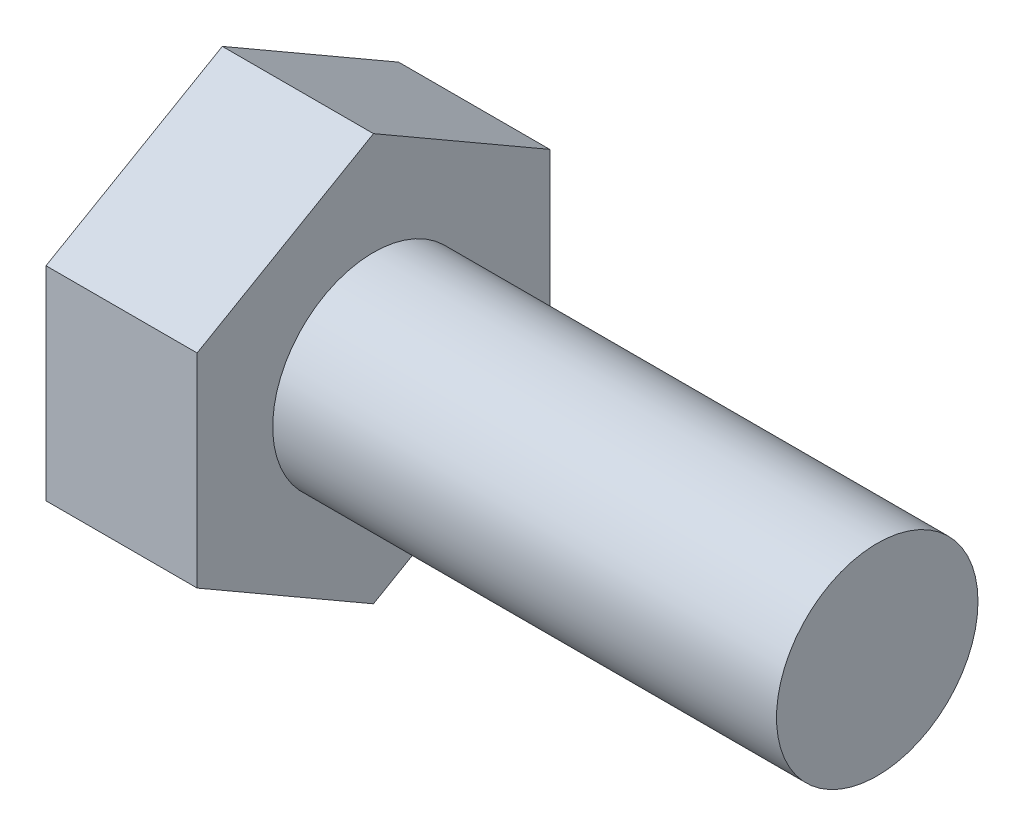
SolidWorks part; units mm, degrees
material "Brass"
ref_plane "Front Plane" through (0, 0, 0) normal (0, 0, 1) x (1, 0, 0)
ref_plane "Top Plane" through (0, 0, 0) normal (0, 1, 0) x (1, 0, 0)
ref_plane "Right Plane" through (0, 0, 0) normal (1, 0, 0) x (0, 0, -1)
sketch "Sketch1" plane through (0, 0, 0) normal (1, 0, 0) x (0, 0, -1)
  circle A0 centre (0, 0) radius 2
  dimension "D1" = 4
extrude "Threaded_Screw" add sketch "Sketch1" along normal blind 10
sketch "Sketch2" plane through (0, 0, 0) normal (-1, 0, 0) x (0, 0, 1)
  line L0 (0, -4.4456) -> (0, 4.4456) construction
  line L1 (3.5, -2.0207) -> (3.5, 2.0207)
  line L2 (3.5, 2.0207) -> (0, 4.0415)
  line L3 (0, 4.0415) -> (-3.5, 2.0207)
  line L4 (-3.5, 2.0207) -> (-3.5, -2.0207)
  line L5 (-3.5, -2.0207) -> (0, -4.0415)
  line L6 (0, -4.0415) -> (3.5, -2.0207)
  circle A0 centre (0, 0) radius 3.5 construction
  dimension "D1" = 7
extrude "Hex_Head" add sketch "Sketch2" along normal blind 3
